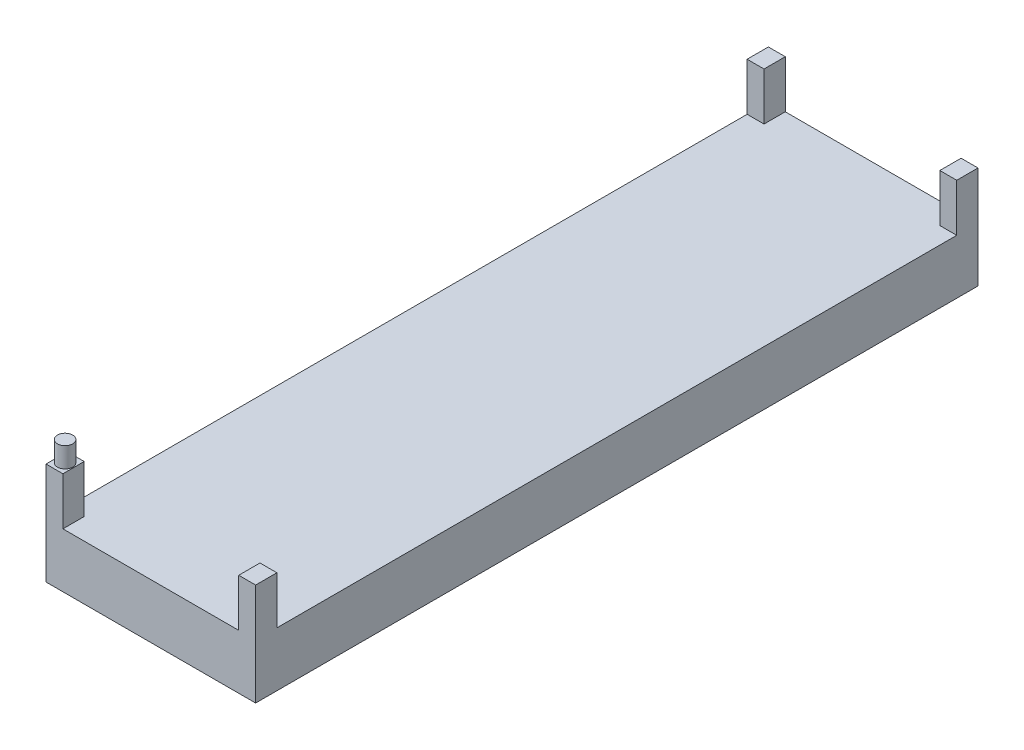
SolidWorks part; units mm, degrees
ref_plane "Front Plane" through (0, 0, 0) normal (0, 0, 1) x (1, 0, 0)
ref_plane "Top Plane" through (0, 0, 0) normal (0, 1, 0) x (1, 0, 0)
ref_plane "Right Plane" through (0, 0, 0) normal (1, 0, 0) x (0, 0, -1)
sketch "Sketch1" plane through (0, 0, 0) normal (0, 1, 0) x (1, 0, 0)
  line L1 (-48.8315, 168.275) -> (48.8315, 168.275)
  line L2 (-48.8315, 168.275) -> (-48.8315, -168.275)
  line L3 (-48.8315, -168.275) -> (48.8315, -168.275)
  line L4 (48.8315, 168.275) -> (48.8315, -168.275)
  line L5 (-55, 0) -> (55, 0) construction
  line L6 (0, -55) -> (0, 55) construction
  point P4 (0, 168.275)
  point P7 (-48.8315, 0)
  dimension "D1" = 336.55
  dimension "D2" = 97.663
extrude "Base" add sketch "Sketch1" along normal blind 25.4
sketch "Sketch2" plane through (0, 25.4, 0) normal (0, 1, 0) x (1, 0, 0)
  line L0 (-1000, 0) -> (49000, 0) construction
  line L1 (-48.8315, -168.275) -> (-40.9575, -168.275)
  line L2 (-48.8315, -168.275) -> (-48.8315, -158.369)
  line L3 (-48.8315, -158.369) -> (-40.9575, -158.369)
  line L4 (-40.9575, -168.275) -> (-40.9575, -158.369)
  line L5 (48.8315, -168.275) -> (40.9575, -168.275)
  line L6 (48.8315, -168.275) -> (48.8315, -158.369)
  line L7 (48.8315, -158.369) -> (40.9575, -158.369)
  line L8 (40.9575, -168.275) -> (40.9575, -158.369)
  line L9 (40.9575, 168.275) -> (40.9575, 158.369)
  line L10 (48.8315, 158.369) -> (40.9575, 158.369)
  line L11 (48.8315, 168.275) -> (48.8315, 158.369)
  line L12 (48.8315, 168.275) -> (40.9575, 168.275)
  line L13 (-40.9575, 168.275) -> (-40.9575, 158.369)
  line L14 (-48.8315, 158.369) -> (-40.9575, 158.369)
  line L15 (-48.8315, 168.275) -> (-48.8315, 158.369)
  line L16 (-48.8315, 168.275) -> (-40.9575, 168.275)
  dimension "D1" = 9.906
  dimension "D2" = 7.874
extrude "Boss-Extrude2" add sketch "Sketch2" along normal blind 22.225
sketch "Sketch3" plane through (0, 47.625, 0) normal (0, 1, 0) x (1, 0, 0)
  line L0 (-1040.9575, -163.322) -> (48959.0425, -163.322) construction
  line L1 (-1000, 0) -> (49000, 0) construction
  line L2 (-40.9575, -168.275) -> (-40.9575, -158.369) construction
  line L3 (-44.8945, -1158.369) -> (-44.8945, 48841.631) construction
  line L4 (-40.9575, -158.369) -> (-48.8315, -158.369) construction
  line L5 (0, -1000) -> (0, 49000) construction
  circle A0 centre (-44.8945, -163.322) radius 3.556
  point P13 (-40.9575, -163.322)
  point P18 (-44.8945, -158.369)
  dimension "D1" = 7.112
extrude "Boss-Extrude3" add sketch "Sketch3" along normal blind 9.398
